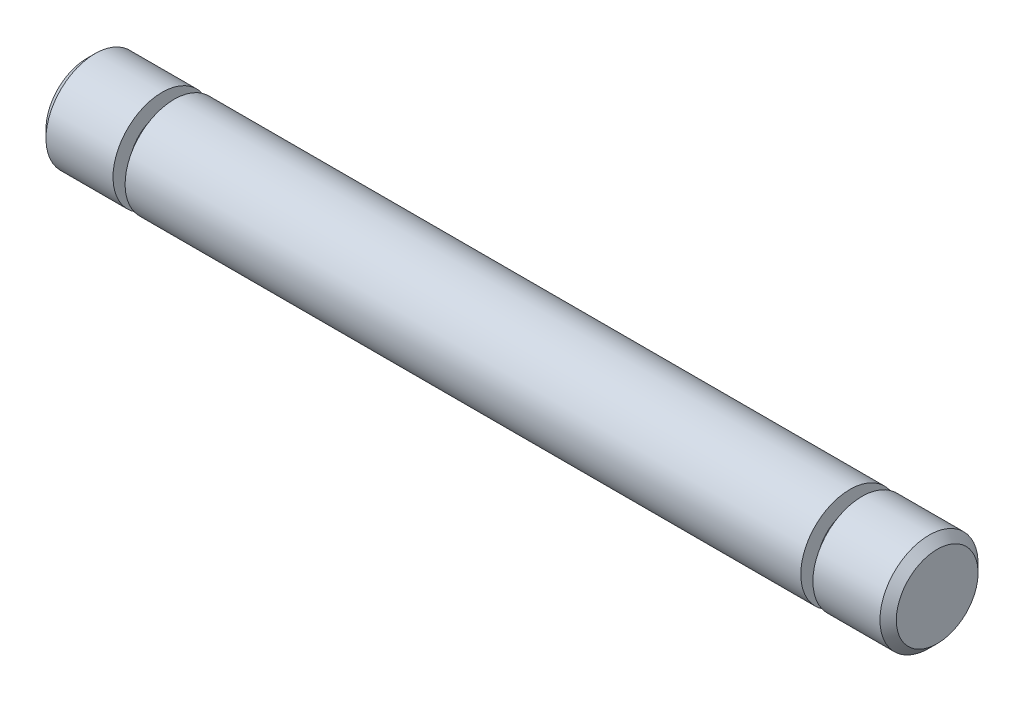
SolidWorks part; units mm, degrees
ref_plane "Plan de face" through (0, 0, 0) normal (0, 0, 1) x (1, 0, 0)
ref_plane "Plan de dessus" through (0, 0, 0) normal (0, 1, 0) x (1, 0, 0)
ref_plane "Plan de droite" through (0, 0, 0) normal (1, 0, 0) x (0, 0, -1)
sketch "Esquisse1" plane through (0, 0, 0) normal (0, 0, 1) x (1, 0, 0)
  line L0 (0, 0) -> (12.8037, 0) construction
  line L1 (0, 0) -> (0, 15.5366) construction
  line L2 (26, 0) -> (-26, 0)
  line L4 (-26, 0) -> (-26, 3)
  line L5 (-26, 3) -> (26, 3)
  line L6 (26, 0) -> (26, 3)
  point P10 (0, 0)
  dimension "D1" = 52
  dimension "D2" = 3
revolve "Révolution1" add sketch "Esquisse1" angle 360 about L0
chamfer "Chanfrein1" distance 0.5 angle 45 2 edges at (-26, 0, 3) (26, 0, 3)
sketch "Esquisse2" plane through (0, 0, 0) normal (0, 0, 1) x (1, 0, 0)
  line L0 (25.5, 3) -> (-25.5, 3) construction
  line L1 (25.5, 3) -> (-25.5, 3)
  line L3 (-10.1, 4) -> (-6.1, 4)
  line L4 (-10.1, 4) -> (-10.1, 2)
  line L5 (-10.1, 2) -> (-6.1, 2)
  line L6 (-6.1, 4) -> (-6.1, 2)
  line L7 (-10.1, 4) -> (-6.1, 2) construction
  line L8 (-10.1, 2) -> (-6.1, 4) construction
  point P2 (-8.1, 3)
  dimension "D1" = 1
  dimension "D2" = 8.1
  dimension "D3" = 4
extrude "Enlèv. mat.-Extru.1" [suppressed] cut sketch "Esquisse2" against normal through all both and the other way through all contours L5 L6 L3 L4
sketch "Esquisse3" plane through (0, 0, 0) normal (0, 0, 1) x (1, 0, 0)
  line L2 (25.5, 3) -> (-25.5, 3) construction
  line L3 (-21.4, 3) -> (-20.66, 3)
  line L4 (0, 0) -> (0, 10.3249) construction
  line L5 (-21.4, 3) -> (-21.4, 2)
  line L6 (-21.4, 2) -> (-20.66, 2)
  line L7 (-20.66, 3) -> (-20.66, 2)
  line L8 (20.66, 3) -> (20.66, 2)
  line L9 (21.4, 2) -> (20.66, 2)
  line L10 (21.4, 3) -> (21.4, 2)
  line L11 (21.4, 3) -> (20.66, 3)
  line L17 (0, 0) -> (-35.8372, 0) construction
  dimension "D1" = 0.74
  dimension "D2" = 2
  dimension "D3" = 42.8
revolve "Enlèvement de matière-Révolution1" cut sketch "Esquisse3" angle 360 about L17
